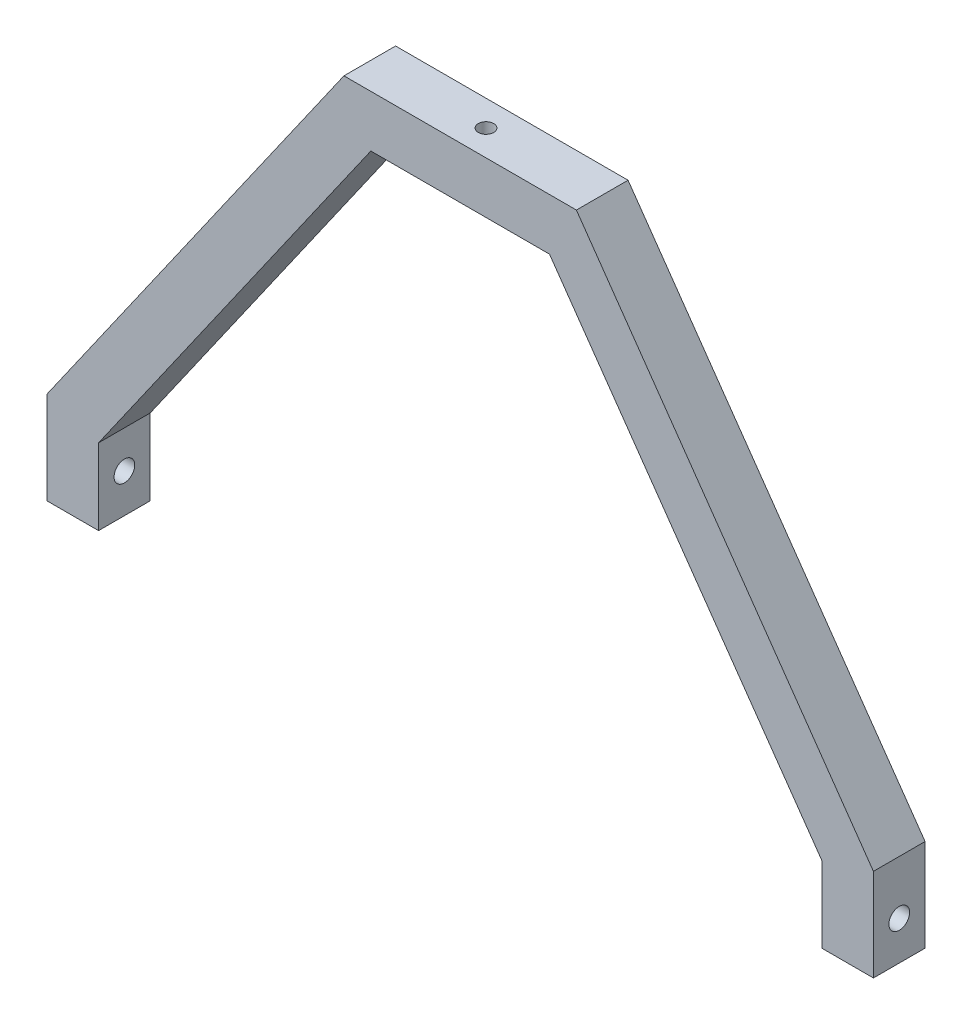
SolidWorks part; units mm, degrees
ref_plane "Ön Düzlem" through (0, 0, 0) normal (0, 0, 1) x (1, 0, 0)
ref_plane "Üst Düzlem" through (0, 0, 0) normal (0, 1, 0) x (1, 0, 0)
ref_plane "Sağ Düzlem" through (0, 0, 0) normal (1, 0, 0) x (0, 0, -1)
sketch "Sketch1" plane through (0, 0, 0) normal (0, 0, 1) x (1, 0, 0)
  line L0 (0, 0) -> (39.7943, 0) construction
  line L1 (39.7943, 0) -> (150, -157.39) construction
  line L2 (150, -157.39) -> (150, -190) construction
  line L3 (0, -10) -> (34.5887, -10)
  line L4 (34.5887, -10) -> (140, -160.543)
  line L5 (140, -160.543) -> (140, -190)
  line L6 (0, 10) -> (45, 10)
  line L7 (45, 10) -> (160, -154.237)
  line L8 (160, -154.237) -> (160, -190)
  line L9 (0, -10) -> (0, 10) construction
  line L10 (140, -190) -> (160, -190)
  line L11 (-140, -190) -> (-160, -190)
  line L12 (-160, -154.237) -> (-160, -190)
  line L13 (-140, -160.543) -> (-140, -190)
  line L14 (0, -10) -> (-34.5887, -10)
  line L15 (-34.5887, -10) -> (-140, -160.543)
  line L16 (-45, 10) -> (-160, -154.237)
  line L17 (0, 10) -> (-45, 10)
  point P9 (-150, -190)
  dimension "D3" = 200
  dimension "D4" = 300
  dimension "D5" = 35
  dimension "D6" = 90
  dimension "D1" = 10
  dimension "D2" = 10
extrude "Boss-Extrude1" add sketch "Sketch1" along normal blind 20
sketch "Sketch2" plane through (160, 0, 0) normal (1, 0, 0) x (0, 0, -1)
  line L0 (-20, -190) -> (0, -190) construction
  circle A0 centre (-10, -175) radius 4
  point P2 (-10, -190)
  dimension "D1" = 8
  dimension "D2" = 15
extrude "Cut-Extrude1" cut sketch "Sketch2" against normal up to surface (320 mm away) up to face at (-160, -172.1185, 10)
sketch "Sketch3" plane through (0, 10, 0) normal (0, 1, 0) x (1, 0, 0)
  line L0 (0, 0) -> (0, -20)
  line L1 (45, -20) -> (-45, -20) construction
  line L2 (-45, -10) -> (45, -10)
  line L3 (-45, -20) -> (-45, 0) construction
  line L4 (45, -20) -> (45, 0) construction
  circle A0 centre (0, -10) radius 3
  dimension "D1" = 6
extrude "Cut-Extrude2" cut sketch "Sketch3" against normal up to surface (20 mm away) contours L0 A0 L2 | L2 A0 L0 | L0 A0 L2 | L2 A0 L0 up to face at (0, -10, 10)
